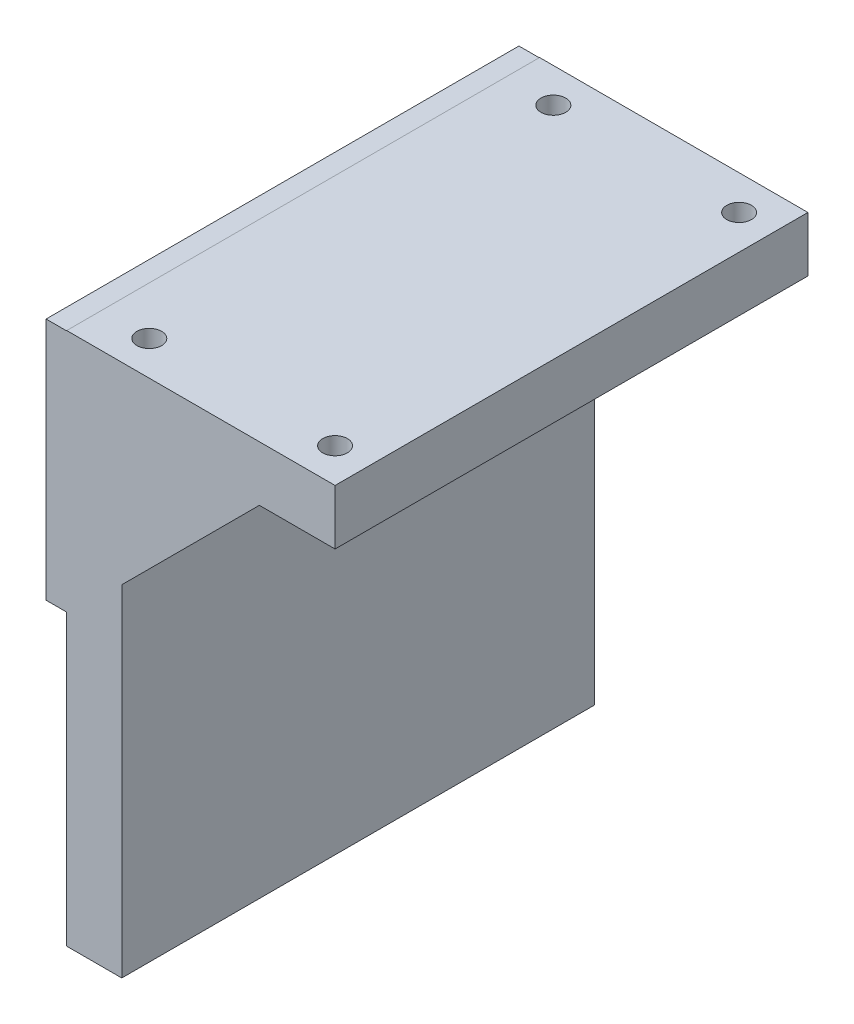
SolidWorks part; units mm, degrees
ref_plane "Front" through (0, 0, 0) normal (0, 0, 1) x (1, 0, 0)
ref_plane "Top" through (0, 0, 0) normal (0, 1, 0) x (1, 0, 0)
ref_plane "Right" through (0, 0, 0) normal (1, 0, 0) x (0, 0, -1)
sketch "Sketch1" plane through (0, 0, 10) normal (0, 0, 1) x (1, 0, 0)
  line L0 (24.3621, 0) -> (24.3621, 77.4964)
  line L1 (63.3621, 77.4964) -> (21.3621, 77.4964) construction
  line L2 (24.3621, 77.4964) -> (63.3621, 77.4964)
  line L3 (32.3621, 0) -> (32.3621, 69.4964)
  line L4 (32.3621, 69.4964) -> (63.3621, 69.4964)
  line L5 (24.3621, 0) -> (32.3621, 0)
  line L6 (63.3621, 69.4964) -> (63.3621, 77.4964)
  line L7 (63.3621, 83.4964) -> (63.3621, 77.4964) construction
  line L8 (18.3621, 0) -> (24.3621, 0) construction
  line L9 (24.3621, 0) -> (24.3621, 42) construction
  point P14 (0, 0)
  point P15 (30.6179, 74.4964)
  dimension "D1" = 8
extrude "Boss-Extrude1" add sketch "Sketch1" against normal up to surface (68.7243 mm away) contours L4 L6 L2 L0 L5 L3
sketch "Sketch4" plane through (0, 0, 10) normal (0, 0, 1) x (1, 0, 0)
  line L1 (32.3621, 0) -> (32.3621, 69.4964) construction
  line L4 (24.3621, 42) -> (32.3621, 42) construction
  line L5 (24.3621, 0) -> (24.3621, 77.4964) construction
  line L6 (18.3621, 42) -> (24.3621, 42) construction
  line L7 (32.3621, 49.4964) -> (32.3621, 69.4964)
  line L8 (32.3621, 69.4964) -> (52.3621, 69.4964)
  line L9 (52.3621, 69.4964) -> (32.3621, 49.4964)
  dimension "D1" = 20
extrude "Boss-Extrude2" add sketch "Sketch4" against normal up to surface (68.7243 mm away) up to face at (40.0288, 48.9976, -58.7243)
sketch "Sketch2" plane through (0, 77.4964, 0) normal (0, 1, 0) x (1, 0, 0)
  circle A0 centre (58.3621, 53.7243) radius 1.8
  circle A1 centre (31.3621, 53.7243) radius 1.8
  circle A2 centre (58.3621, -5) radius 1.8
  circle A3 centre (31.3621, -5) radius 1.8
  dimension "D1" = 3.6
extrude "Cut-Extrude1" cut sketch "Sketch2" against normal blind 6
sketch "Sketch3" plane through (24.3621, 0, 0) normal (-1, 0, 0) x (0, 0, 1)
  circle A0 centre (-53.7243, 37) radius 1.8
  circle A1 centre (-53.7243, 10) radius 1.8
  circle A2 centre (5, 10) radius 1.8
  circle A3 centre (5, 37) radius 1.8
  dimension "D1" = 3.6
extrude "Cut-Extrude2" cut sketch "Sketch3" against normal blind 6
sketch "Sketch5" plane through (24.3621, 0, 0) normal (-1, 0, 0) x (0, 0, 1)
  line L0 (-58.7243, 0) -> (-58.7243, 77.4964) construction
  line L1 (-58.7243, 77.4464) -> (10, 77.4464)
  line L2 (-58.7243, 77.4464) -> (-58.7243, 42.05)
  line L3 (-58.7243, 42.05) -> (10, 42.05)
  line L4 (10, 77.4464) -> (10, 42.05)
  line L5 (10, 0) -> (10, 77.4964) construction
  line L6 (10, 42) -> (0, 42) construction
  line L7 (-58.7243, 77.4964) -> (10, 77.4964) construction
  dimension "D1" = 0.05
  dimension "D2" = 0.05
extrude "Boss-Extrude3" add sketch "Sketch5" along normal up to vertex (3 mm away)
